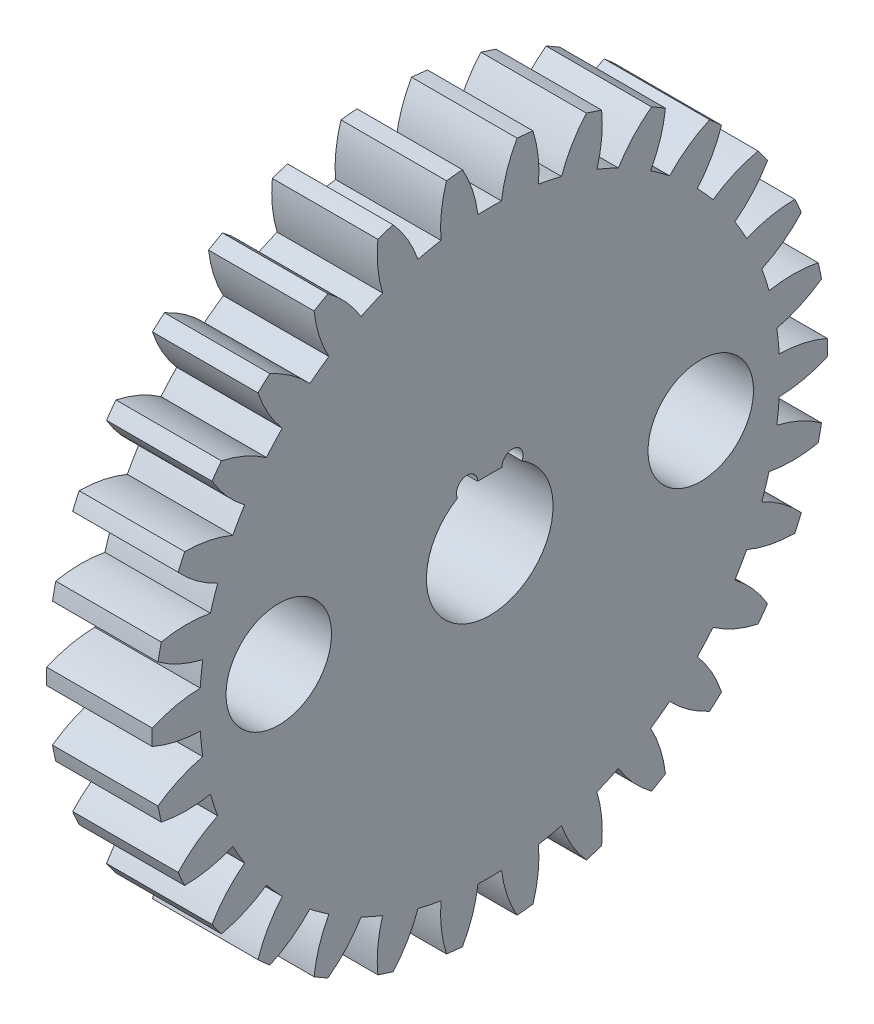
SolidWorks part; units mm, degrees
ref_plane "Plane1" through (0, 0, 0) normal (0, 0, 1) x (1, 0, 0)
ref_plane "Plane2" through (0, 0, 0) normal (0, 1, 0) x (1, 0, 0)
ref_plane "Plane3" through (0, 0, 0) normal (1, 0, 0) x (0, 0, -1)
sketch "HoldingSke" plane through (0, 0, 0) normal (0, 1, 0) x (1, 0, 0)
  line L0 (0, 0) -> (1.7321, -1)
  line L1 (-15, 0) -> (100, 0) construction
  line L2 (0, 0) -> (-2.1039, 2.3779)
  line L3 (0, 0) -> (-11.863, 4.5341)
  line L4 (0, 0) -> (7.479, 4.318)
  line L5 (0, 0) -> (-46.8476, -17.4728)
  line L6 (0, 0) -> (-2.0724, -1.3983)
  line L7 (-2.1039, 2.3779) -> (8.6586, 51.2059)
  line L8 (-76.2, 54.61) -> (-75.7, 54.61)
  line L9 (-67.7845, 28.3722) -> (-49.3413, 33.142)
  line L10 (-76.2, 71.12) -> (104.1128, 71.12)
  line L11 (0, 0) -> (-2.5, 0)
  line L12 (-76.2, 101.6) -> (-76.181, 101.6)
  line L13 (24.9733, 27.94) -> (52.9518, 28.4284)
  line L14 (24.9733, 27.94) -> (24.9743, 27.94)
  line L15 (24.9733, 27.94) -> (100.4006, 29.5858)
  line L16 (-63.627, -0.5) -> (-12.827, -0.5)
  circle A0 centre (0, 0) radius 1.5
  circle A1 centre (0, 0) radius 6.874
  circle A2 centre (0, 0) radius 37.5
  circle A3 centre (0, 0) radius 1.5
  dimension "MHD" = 13.748
  dimension "Hub_dia" = 75
  dimension "Bore" = 3
  dimension "MBD" = 3
  dimension "Num_teeth" = 30
  dimension "Pitch" = 2
  dimension "Overall_len" = 50
  dimension "Show_teeth" = 30
  dimension "Thickness" = 2.5
  dimension "OAL" = 50.0001
  dimension "T_dim" = 0.5
  dimension "Ap" = 14.5
  dimension "H" = 19.05
  dimension "Pitch_radius" = 180.3128
  dimension "Width" = 2.5
  dimension "Backlash" = 0.019
  dimension "Addendum_fac" = 1
  dimension "Dedendum_fac" = 1.25
  dimension "Clearance_fac" = 0.25
  dimension "Dedendum_add" = 0.001
  dimension "Module" = 0.5
sketch "BasProSke" plane through (0, 0, 0) normal (0, 1, 0) x (1, 0, 0)
  line L0 (-10, 0) -> (60, 0) construction
  line L1 (0, 0) -> (0, 8)
  line L2 (0, 0) -> (2.5, 0)
  line L3 (2.5, 0) -> (2.5, 8)
  line L4 (2.5, 8) -> (0, 8)
  dimension "Thickness" = 2.5
  dimension "Diameter" = 16
revolve "Base-Revolve" add sketch "BasProSke" angle 360 about L0
sketch "TooCutSke" plane through (0, 0, 0) normal (1, 0, 0) x (0, 0, -1)
  line L1 (0, 0) -> (0, 107) construction
  line L2 (0, 0) -> (-0.4258, 7.4879) construction
  line L3 (0, 0) -> (-1.5661, 14.9007) construction
  line L4 (-0.4258, 7.4879) -> (-0.7831, 7.4504) construction
  arc A0 (0.279, 6.8683) -> (-0.279, 6.8683) centre (0, 0) ccw
  arc A1 (0.6614, 7.9981) -> (-0.6614, 7.9981) centre (0, 0) ccw
  circle A2 centre (0, 0) radius 7.5 construction
  circle A3 centre (0, 0) radius 7.2611 construction
  arc A4 (-0.279, 6.8683) -> (-0.6614, 7.9981) centre (-3.2551, 6.4906) ccw
  arc A5 (0.6614, 7.9981) -> (0.279, 6.8683) centre (3.2551, 6.4906) ccw
  dimension "Root_dia" = 13.748
  dimension "Overcut_dia" = 16.0508
  dimension "Pitch_dia" = 15
  dimension "Base_dia" = 14.5222
  dimension "Flank_rad" = 3
  dimension "Half_ang" = 6
  dimension "Half_CT" = 0.3593
extrude "ToothCut" cut sketch "TooCutSke" along normal through all
fillet "Breaks" [suppressed] radius 0.01
fillet "RootFillets" [suppressed] radius 0.126
pattern_circular "TeethCuts" count 30 every 12 about axis through (-10, 0, 0) along (1, 0, 0) of "ToothCut", "RootFillets", "Breaks"
sketch "HubNeaOneSke" plane through (0, 0, 0) normal (-1, 0, 0) x (0, 0, 1)
  circle A0 centre (0, 0) radius 6.874
  dimension "Diameter" = 13.748
extrude "HubNearOne" [suppressed] add sketch "HubNeaOneSke" along normal blind 47.5001
sketch "HubNeaBotSke" plane through (0, 0, 0) normal (-1, 0, 0) x (0, 0, 1)
  circle A0 centre (0, 0) radius 6.874
  dimension "Diameter" = 13.748
extrude "HubNearBoth" [suppressed] add sketch "HubNeaBotSke" along normal blind 23.75
ref_plane "FarPln" through (2.5, 0, 0) normal (1, 0, 0) x (0, 0, -1)
sketch "HubFarSke" plane through (2.5, 0, 0) normal (1, 0, 0) x (0, 0, -1)
  circle A0 centre (0, 0) radius 6.874
  dimension "Diameter" = 13.748
extrude "HubFar" [suppressed] add sketch "HubFarSke" along normal blind 23.75
sketch "BorSke" plane through (0, 0, 0) normal (1, 0, 0) x (0, 0, -1)
  circle A0 centre (0, 0) radius 1.5
  dimension "Diameter" = 3
extrude "Bore" cut sketch "BorSke" along normal mid plane 100.0001
sketch "KeySke" plane through (0, 0, 0) normal (1, 0, 0) x (0, 0, -1)
  line L0 (-0.6, 0) -> (-0.6, 2)
  line L1 (-0.6, 2) -> (0.6, 2)
  line L2 (0.6, 2) -> (0.6, 0)
  line L3 (0, 0) -> (0, 34) construction
  line L4 (-0.6, 0) -> (0.6, 0)
  dimension "Offset" = 2
  dimension "Width" = 1.2
extrude "Keyway" [suppressed] cut sketch "KeySke" along normal mid plane 100.0001
pattern_circular "Keyway2" [suppressed] count 2 every 90 about axis through (-10, 0, 0) along (1, 0, 0)
sketch "草图3" plane through (0, 0, 0) normal (-1, 0, 0) x (0, 0, 1)
  circle A0 centre (-5, 0) radius 1.25
  circle A1 centre (5, 0) radius 1.25
  dimension "D1" = 10
extrude "切除-拉伸1" cut sketch "草图3" against normal through all
sketch "草图4" plane through (0, 0, 0) normal (-1, 0, 0) x (0, 0, 1)
  line L1 (-0.5385, 1.4) -> (0.5385, 1.4)
  arc A0 (0.5385, 1.4) -> (-0.5385, 1.4) centre (0, 0) ccw
extrude "凸台-拉伸1" add sketch "草图4" against normal through all
sketch "草图5" plane through (0, 0, 0) normal (-1, 0, 0) x (0, 0, 1)
  circle A0 centre (-0.5385, 1.4) radius 0.25
  circle A1 centre (0.5385, 1.4) radius 0.25
extrude "切除-拉伸2" cut sketch "草图5" against normal through all
equation "' \"Module@HoldingSke\" = 6.35"
equation "' \"Num_teeth@HoldingSke\" = 12"
equation "' \"Ap@HoldingSke\" =  20"
equation "' \"Ap@HoldingSke\" = 20"
equation "' \"Width@HoldingSke\" = 0.5 * 25.4"
equation "' \"Hub_dia@HoldingSke\"= 1 * 25.4"
equation "' \"Hub_dia@HoldingSke\" = 1 * 25.4"
equation "' \"Overall_len@HoldingSke\" = 1.0 * 25.4"
equation "' \"Bore@HoldingSke\" = 0.75 * 25.4"
equation "' \"T_dim@HoldingSke\" = 0.1 * 25.4"
equation "' \"Width@KeySke\" = 0.25 * 25.4"
equation "' \"Show_teeth@HoldingSke\" = 13"
equation "' \"Backlash@HoldingSke\" = 0.009 * 25.4"
equation "' \"Addendum_fac@HoldingSke\" = 1.0"
equation "' \"Dedendum_fac@HoldingSke\" = 1.25"
equation "' \"Dedendum_add@HoldingSke\" = 0.00005 * 25.4"
equation "' \"Clearance_fac@HoldingSke\" = 0.25"
equation "\"Pitch@HoldingSke\" = 1 / \"Module@HoldingSke\""
equation "\"Overcut_dia@TooCutSke\" = (\"Num_teeth@HoldingSke\" + 2 * \"Addendum_fac@HoldingSke\") / \"Pitch@HoldingSke\" + 0.002 * 25.4"
equation "\"Pitch_dia@TooCutSke\" = \"Num_teeth@HoldingSke\" / \"Pitch@HoldingSke\""
equation "\"Base_dia@TooCutSke\" = \"Num_teeth@HoldingSke\" / \"Pitch@HoldingSke\" * cos((\"Ap@HoldingSke\"  * 3.14159265 / 180))"
equation "\"Root_dia@TooCutSke\" = (\"Num_teeth@HoldingSke\" + 2) / \"Pitch@HoldingSke\" - 2 * (\"Addendum_fac@HoldingSke\" + \"Dedendum_fac@HoldingSke\") / \"Pitch@HoldingSke\" - \"Dedendum_add@HoldingSke\" * 2"
equation "\"Half_ang@TooCutSke\" = 180 / \"Num_teeth@HoldingSke\""
equation "\"Half_CT@TooCutSke\" = \"Num_teeth@HoldingSke\" / \"Pitch@HoldingSke\" * sin((3.14159265 / 2 / \"Num_teeth@HoldingSke\")) / 2 - 7 * \"Backlash@HoldingSke\" / 4"
equation "\"Flank_rad@TooCutSke\" = \"Num_teeth@HoldingSke\" / \"Pitch@HoldingSke\" / 5"
equation "\"Radius@RootFillets\" = \"Clearance_fac@HoldingSke\" / \"Pitch@HoldingSke\" + \"Dedendum_add@HoldingSke\""
equation "\"Break_rad@Breaks\" = 0.02 / \"Pitch@HoldingSke\""
equation "\"Thickness@HoldingSke\" = \"Width@HoldingSke\""
equation "\"OAL@HoldingSke\" = \"Thickness@HoldingSke\""
equation "\"MHD@HoldingSke\" = (\"Num_teeth@HoldingSke\" + 2) / \"Pitch@HoldingSke\" - 2 * (\"Addendum_fac@HoldingSke\" + \"Dedendum_fac@HoldingSke\")  / \"Pitch@HoldingSke\" - \"Dedendum_add@HoldingSke\" * 2"
equation "\"MBD@HoldingSke\" = (\"Num_teeth@HoldingSke\" + 2) / \"Pitch@HoldingSke\" - 2 * (\"Addendum_fac@HoldingSke\" + \"Dedendum_fac@HoldingSke\")  / \"Pitch@HoldingSke\" - \"Dedendum_add@HoldingSke\" * 2 - 0.002 * 25.4"
equation "\"MHD@HoldingSke\" = ((sgn( \"MHD@HoldingSke\" - \"Hub_dia@HoldingSke\" )-1)*( \"MHD@HoldingSke\" - \"Hub_dia@HoldingSke\" ))/-2+ \"Hub_dia@HoldingSke\""
equation "\"MBD@HoldingSke\" = ((sgn( \"MBD@HoldingSke\" - \"Bore@HoldingSke\" )-1)*( \"MBD@HoldingSke\" - \"Bore@HoldingSke\" ))/-2+ \"Bore@HoldingSke\""
equation "\"OAL@HoldingSke\" = ((sgn( \"OAL@HoldingSke\" - \"Overall_len@HoldingSke\" )+1)*( \"OAL@HoldingSke\" - \"Overall_len@HoldingSke\" ))/2 + \"Overall_len@HoldingSke\" + 0.000002 * 25.4"
equation "\"Num_teeth@TeethCuts\" = int( \"Show_teeth@HoldingSke\" ) + 1"
equation "\"Num_teeth@TeethCuts\" = ((sgn( \"Num_teeth@TeethCuts\" - \"Num_teeth@HoldingSke\" )-1)*( \"Num_teeth@TeethCuts\" - \"Num_teeth@HoldingSke\" ))/-2+ \"Num_teeth@HoldingSke\""
equation "\"Num_teeth@TeethCuts\" = ((sgn( \"Num_teeth@TeethCuts\" - 2.0)+1)*( \"Num_teeth@TeethCuts\" - 2.0))/2 +2.0"
equation "\"Angle@TeethCuts\" = 360.0 / \"Num_teeth@HoldingSke\""
equation "\"Diameter@BasProSke\" = (\"Num_teeth@HoldingSke\" + 2 * \"Addendum_fac@HoldingSke\") / \"Pitch@HoldingSke\""
equation "\"Thickness@BasProSke\"  = \"Thickness@HoldingSke\""
equation "' \"Fillet_rad@BasProSke\" =  \"Thickness@HoldingSke\" * 0.05"
equation "' \"Fillet_rad@BasProSke\" = \"Thickness@HoldingSke\" * 0.05"
equation "\"MHD@HoldingSke\" = ((sgn( \"MHD@HoldingSke\" - \"Root_dia@TooCutSke\" )-1)*( \"MHD@HoldingSke\" - \"Root_dia@TooCutSke\" ))/-2+ \"Root_dia@TooCutSke\""
equation "\"Diameter@HubNeaOneSke\" = \"MHD@HoldingSke\""
equation "\"Length@HubNearOne\" = \"OAL@HoldingSke\" - \"Thickness@BasProSke\""
equation "\"Diameter@HubNeaBotSke\" = \"MHD@HoldingSke\""
equation "\"Length@HubNearBoth\" = ( \"OAL@HoldingSke\" - \"Thickness@BasProSke\" ) / 2.0"
equation "\"Thickness@FarPln\" = \"Thickness@BasProSke\""
equation "\"Diameter@HubFarSke\" = \"MHD@HoldingSke\""
equation "\"Length@HubFar\" = ( \"OAL@HoldingSke\" - \"Thickness@BasProSke\" ) / 2.0"
equation "\"Diameter@BorSke\" = \"MBD@HoldingSke\""
equation "\"D1@Bore\" = \"OAL@HoldingSke\" * 2.0"
equation "\"D1@Keyway\" = \"OAL@HoldingSke\" * 2.0"
equation "\"Offset@KeySke\" = \"T_dim@HoldingSke\" + \"MBD@HoldingSke\" / 2.0"
